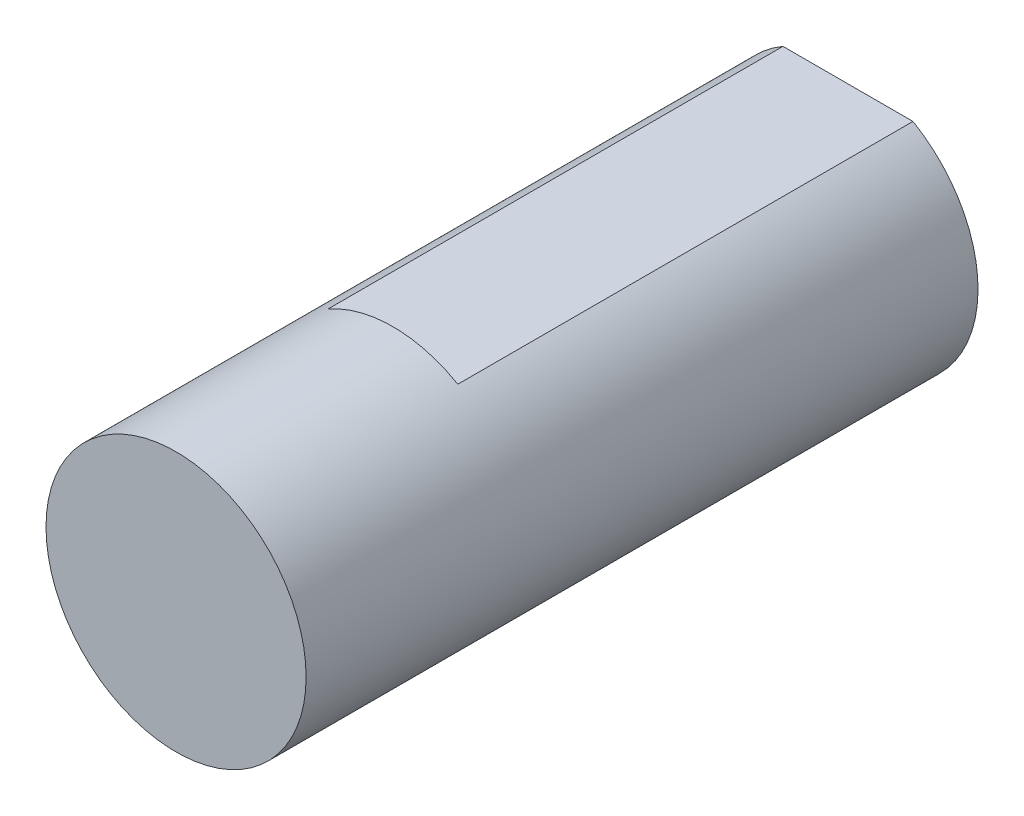
SolidWorks part; units mm, degrees
ref_plane "Front Plane" through (0, 0, 0) normal (0, 0, 1) x (1, 0, 0)
ref_plane "Top Plane" through (0, 0, 0) normal (0, 1, 0) x (1, 0, 0)
ref_plane "Right Plane" through (0, 0, 0) normal (1, 0, 0) x (0, 0, -1)
sketch "Sketch1" plane through (0, 0, 0) normal (0, 0, 1) x (1, 0, 0)
  line L0 (-3, 5.1962) -> (3, 5.1962)
  circle A0 centre (0, 0) radius 6
  dimension "D1" = 12
  dimension "D2" = 6
extrude "Boss-Extrude1" add sketch "Sketch1" along normal blind 31 contours A0
sketch "Sketch2" plane through (0, 0, 0) normal (0, 0, -1) x (-1, 0, 0)
  line L0 (-3, 5.1962) -> (3, 5.1962)
  circle A1 centre (0, 0) radius 6 construction
  circle A2 centre (0, 0) radius 6
  circle M3 centre (0, 0) radius 6
  dimension "D1" = 6
extrude "Cut-Extrude1" cut sketch "Sketch2" against normal blind 21 contours L0 M3
